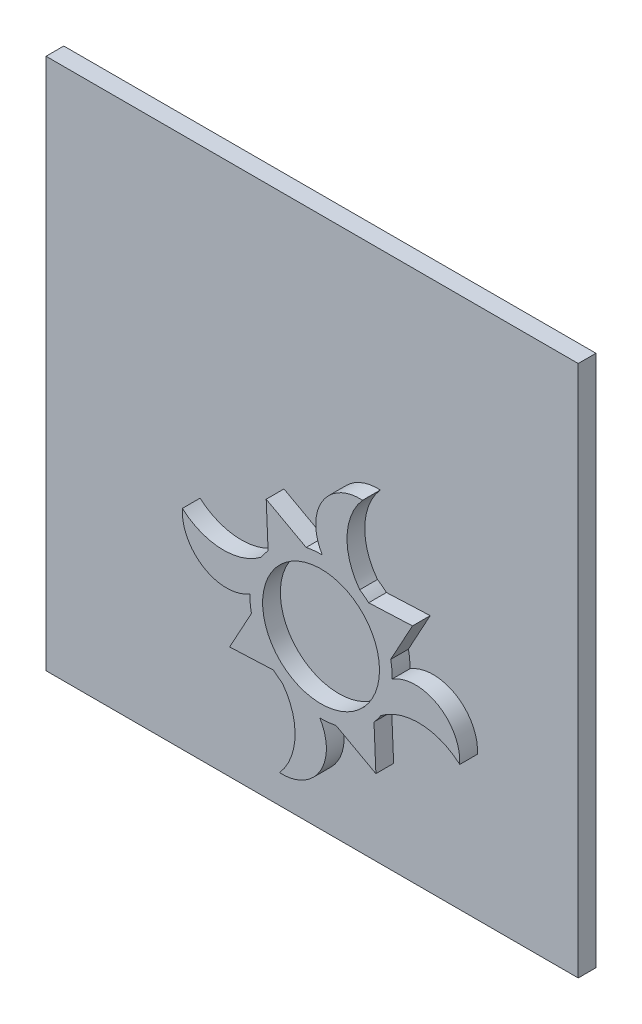
SolidWorks part; units mm, degrees
material "Obyčejná uhlíková ocel"
ref_plane "Přední rovina" through (0, 0, 0) normal (0, 0, 1) x (1, 0, 0)
ref_plane "Horní rovina" through (0, 0, 0) normal (0, 1, 0) x (1, 0, 0)
ref_plane "Pravá rovina" through (0, 0, 0) normal (1, 0, 0) x (0, 0, -1)
sketch "Skica1" plane through (0, 0, 0) normal (0, 0, 1) x (1, 0, 0)
  line L1 (0, 0) -> (300, 0)
  line L2 (0, 0) -> (0, 300)
  line L3 (0, 300) -> (300, 300)
  line L4 (300, 0) -> (300, 300)
  dimension "D1" = 300
extrude "Přidat vysunutím1" add sketch "Skica1" along normal blind 10
sketch "Skica3" plane through (0, 0, 10) normal (0, 0, 1) x (1, 0, 0)
  line L2 (135.179, 131.1048) -> (134.1143, 155.8104)
  line L3 (134.1143, 155.8104) -> (156.618, 143.5175)
  line L4 (191.8587, 134.1208) -> (216.5643, 135.1855)
  line L5 (216.5643, 135.1855) -> (204.2714, 112.6818)
  line L6 (194.8747, 77.4411) -> (195.9394, 52.7355)
  line L7 (195.9394, 52.7355) -> (173.4357, 65.0284)
  line L8 (138.195, 74.4251) -> (113.4894, 73.3604)
  line L9 (113.4894, 73.3604) -> (125.7823, 95.8641)
  circle A95 centre (165.0268, 104.273) radius 32.9412
  arc A96 (188.4383, 182.4632) -> (165.7331, 144.4021) centre (187.0254, 157.5031) ccw
  arc A97 (188.4383, 182.4632) -> (186.8342, 137.9669) centre (214.768, 159.237) ccw
  circle A98 centre (165.0268, 104.273) radius 40.1353
  arc A99 (243.217, 80.8615) -> (198.7208, 82.4656) centre (219.9908, 54.5319) ccw
  arc A100 (243.217, 80.8615) -> (205.1559, 103.5667) centre (218.257, 82.2744) ccw
  arc A101 (141.6154, 26.0828) -> (143.2195, 70.579) centre (115.2857, 49.309) ccw
  arc A102 (141.6154, 26.0828) -> (164.3206, 64.1439) centre (143.0283, 51.0428) ccw
  arc A103 (86.8366, 127.6844) -> (131.3329, 126.0803) centre (110.0629, 154.0141) ccw
  arc A104 (86.8366, 127.6844) -> (124.8978, 104.9792) centre (111.7967, 126.2715) ccw
  point P8 (214.768, 137.9669)
  point P26 (165.0268, 104.273)
  point P34 (156.4285, 144.4021)
  point P35 (134.1143, 131.1048)
  dimension "D1" = 4
  dimension "D2" = 65.8824
  dimension "D3" = 80.2706
  dimension "D4" = 25
extrude "Přidat vysunutím3" add sketch "Skica3" along normal blind 10 contours A98 A95 | A98 L3 L2 | A98 A97 A96 | A98 L5 L4 | A99 A100 A98 | A98 L7 L6 | A101 A102 A98 | A98 L9 L8 | A103 A104 A98
